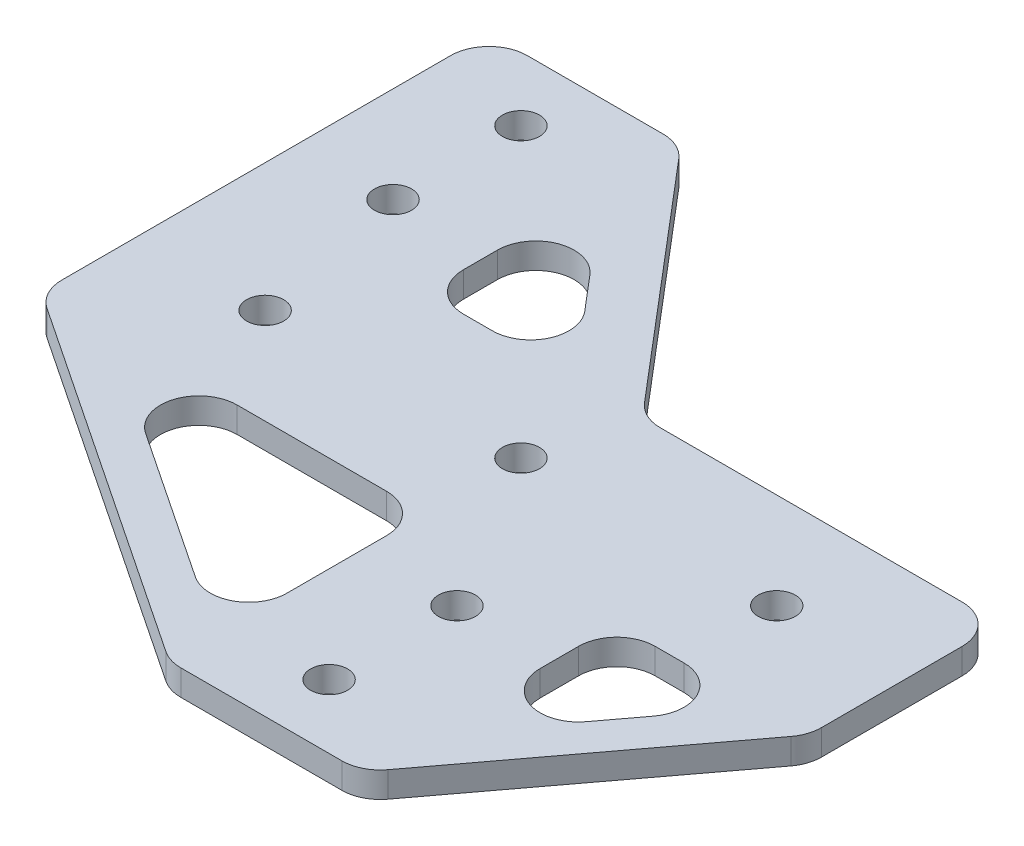
SolidWorks part; units mm, degrees
material "Thornel Mat VMA"
ref_plane "前视基准面" through (0, 0, 0) normal (0, 0, 1) x (1, 0, 0)
ref_plane "上视基准面" through (0, 0, 0) normal (0, 1, 0) x (1, 0, 0)
ref_plane "右视基准面" through (0, 0, 0) normal (1, 0, 0) x (0, 0, -1)
other "Configuration Table"
sketch "草图1" plane through (0, 0, 0) normal (0, 1, 0) x (1, 0, 0)
  line L0 (15, 35) -> (15, 15) construction
  line L1 (0, 0) -> (15, 0) construction
  line L2 (0, 0) -> (0, 35) construction
  line L3 (0, 35) -> (15, 35) construction
  line L4 (15, 0) -> (15, 35) construction
  line L5 (0, 0) -> (60, 0) construction
  line L6 (0, 0) -> (0, 15)
  line L7 (0, 15) -> (60, 15) construction
  line L8 (60, 0) -> (60, 15) construction
  line L9 (30, 15) -> (45, 15) construction
  line L10 (30, 15) -> (30, -20) construction
  line L11 (30, -20) -> (45, -20) construction
  line L12 (45, 15) -> (45, -20) construction
  line L13 (15, 15) -> (30, 15) construction
  line L14 (45, 15) -> (60, 15) construction
  line L15 (15, 0) -> (30, 0) construction
  line L16 (30, 0) -> (30, -20) construction
  line L17 (45, -20) -> (45, 0) construction
  line L18 (45, 0) -> (60, 0) construction
  line L19 (0, 0) -> (30, -20) construction
  line L20 (15, 35) -> (60, 15) construction
  line L21 (60, 0) -> (45, -20) construction
  line L22 (5.4083, 0) -> (30, 0)
  line L23 (30, 0) -> (30, -16.3944)
  line L24 (30, -16.3944) -> (5.4083, 0)
  line L25 (15, 28.8238) -> (15, 15) construction
  line L26 (15, 15) -> (52.6134, 15) construction
  line L28 (56.25, 0) -> (45, -15)
  line L29 (45, -15) -> (45, 0)
  line L30 (45, 0) -> (56.25, 0)
  line L31 (0, 0) -> (30, -20)
  line L32 (30, -20) -> (45, -20)
  line L33 (45, -20) -> (60, 0)
  line L34 (60, 0) -> (60, 15)
  line L35 (60, 15) -> (15, 35) construction
  line L36 (15, 35) -> (0, 35)
  line L37 (0, 35) -> (0, 0)
  line L38 (7.5, 46.7802) -> (7.5, -14.9998) construction
  line L39 (37.5, 36.5055) -> (37.5, -31.8877) construction
  line L40 (-7.4455, 7.5) -> (81.0629, 7.5) construction
  line L43 (26.7502, 15) -> (15, 15)
  line L44 (15, 15) -> (15, 28.8238)
  line L45 (45, 15) -> (60, 15)
  line L46 (15, 28.8238) -> (26.7502, 15)
  line L47 (15, 35) -> (32, 15)
  line L48 (32, 15) -> (45, 15)
  circle A1 centre (10, 7.5) radius 1.45
  circle A2 centre (30, 7.5) radius 1.45
  circle A3 centre (50, 7.5) radius 1.45
  circle A4 centre (7.5, 20) radius 1.45
  circle A5 centre (7.5, 30) radius 1.45
  circle A6 centre (37.5, -5) radius 1.45
  circle A7 centre (37.5, -15) radius 1.45
  point P44 (15, 28.9767)
  dimension "D7" = 2.9
  dimension "D9" = 5
  dimension "D10" = 10
  dimension "D11" = 5
  dimension "D13" = 10
  dimension "D15" = 20
  dimension "D16" = 20
  dimension "D8" = 10
  dimension "D17" = 2.9
  dimension "D18" = 5
  dimension "D1" = 30
  dimension "D2" = 15
  dimension "D3" = 15
  dimension "D4" = 15
  dimension "D5" = 3
  dimension "D6" = 4
  dimension "D12" = 5
  dimension "D14" = 8.55
  dimension "D19" = 3
  dimension "D20" = 17
extrude "凸台-拉伸1" add sketch "草图1" along normal blind 2
fillet "圆角1" radius 3 17 edges at (45, 1, 20) (30, 1, 20) (0, 1, 0) (0, 1, -35) (60, 1, 0) (30, 1, 0) (5.4083, 1, 0) (30, 1, 16.3944) (45, 1, 15) (56.25, 1, 0) (45, 1, 0) (60, 1, -15) (15, 1, -35) (32, 1, -15) (15, 1, -15) (26.7502, 1, -15) (15, 1, -28.8238)
